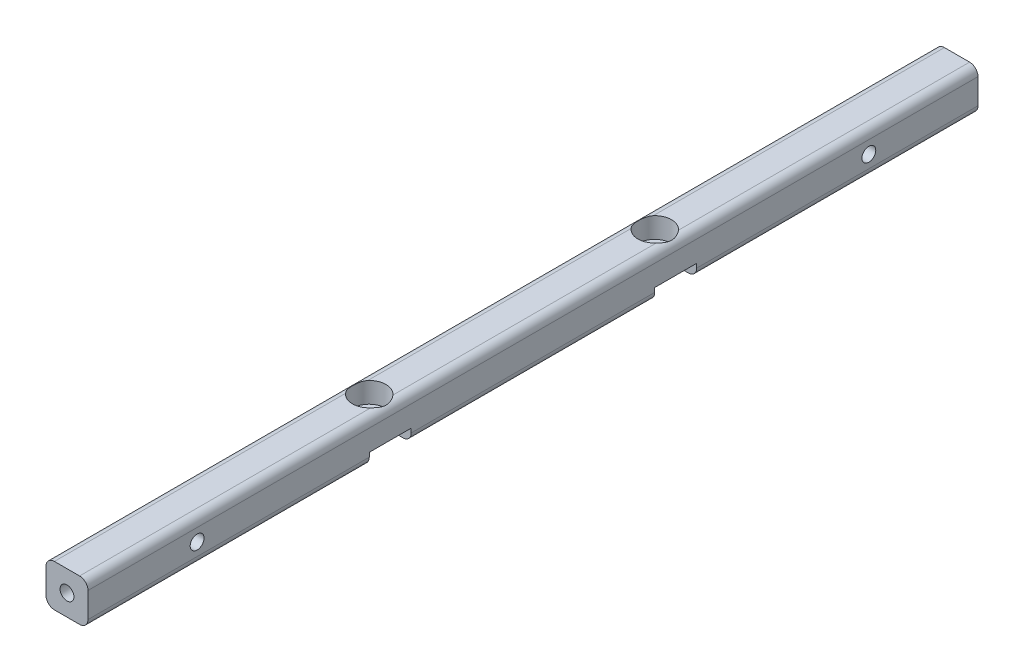
SolidWorks part; units mm, degrees
material "Alliage 1060"
ref_plane "Face" through (0, 0, 0) normal (0, 0, 1) x (1, 0, 0)
ref_plane "Dessus" through (0, 0, 0) normal (0, 1, 0) x (1, 0, 0)
ref_plane "Droite" through (0, 0, 0) normal (1, 0, 0) x (0, 0, -1)
sketch "Esquisse1" plane through (0, 0, 0) normal (0, 0, 1) x (1, 0, 0)
  line L1 (-5, 5) -> (5, 5)
  line L2 (-5, 5) -> (-5, -5)
  line L3 (-5, -5) -> (5, -5)
  line L4 (5, 5) -> (5, -5)
extrude "Boss.-Extru.1" add sketch "Esquisse1" along normal mid plane 212
hole_wizard "Trou taraudé M41" positions "Esquisse3" profile "Esquisse2" tap size "M4" standard "Iso"
sketch "Esquisse3" plane through (0, 0, 106) normal (0, 0, 1) x (1, 0, 0)
  point P0 (0, 0)
sketch "Esquisse2" plane through (0, 0, 106) normal (1, 0, 0) x (0, -1, 0)
  line L0 (0, 0) -> (0, 12.4914)
  line L1 (0, 12.4914) -> (1.65, 11.5)
  line L2 (1.65, 11.5) -> (1.65, 0)
  line L5 (1.65, 0) -> (0, 0)
  line L10 (0, 12.4914) -> (-1.65, 11.5) construction
  line L11 (0, -6.35) -> (0, 107.95) construction
  dimension "Diamètre du trou pour taraudage" = 3.3
  dimension "Profondeur du trou pour taraudage" = 11.5
  dimension "Angle de pointe" = 118
cosmetic thread "Filetage de perçage1" parameters "D1"=8, "D2"=4
hole_wizard "Trou taraudé M42" positions "Esquisse5" profile "Esquisse4" tap size "M4" standard "Iso"
sketch "Esquisse5" plane through (0, 0, -106) normal (0, 0, -1) x (-1, 0, 0)
  point P0 (0, 0)
sketch "Esquisse4" plane through (0, 0, -106) normal (1, 0, 0) x (0, 1, 0)
  line L0 (0, 0) -> (0, 12.4914)
  line L1 (0, 12.4914) -> (1.65, 11.5)
  line L2 (1.65, 11.5) -> (1.65, 0)
  line L5 (1.65, 0) -> (0, 0)
  line L10 (0, 12.4914) -> (-1.65, 11.5) construction
  line L11 (0, -6.35) -> (0, 107.95) construction
  dimension "Diamètre du trou pour taraudage" = 3.3
  dimension "Profondeur du trou pour taraudage" = 11.5
  dimension "Angle de pointe" = 118
cosmetic thread "Filetage de perçage2" parameters "D1"=8, "D2"=4
fillet "Congé1" radius 2 4 edges at (-5, -5, 0) (5, -5, 0) (-5, 5, 0) (5, 5, 0)
hole_wizard "Chambrage pour vis à tête hexagonale M41" positions "Esquisse7" profile "Esquisse6" counterbore size "M4" standard "Iso" end condition through all
sketch "Esquisse7" plane through (0, 5, 0) normal (0, 1, 0) x (1, 0, 0)
  point P0 (0, 34)
  point P13 (0, -34)
  dimension "D1" = 34
  dimension "D2" = 34
sketch "Esquisse6" plane through (0, 5, -34) normal (1, 0, 0) x (0, 0, 1)
  line L0 (0, 0) -> (0, 10)
  line L1 (0, 10) -> (2.15, 10)
  line L3 (2.15, 10) -> (2.15, 4.9)
  line L4 (2.15, 4.9) -> (4, 4.9)
  line L5 (4, 4.9) -> (4, 0)
  line L7 (4, 0) -> (0, 0)
  line L11 (0, -6.35) -> (0, 107.95) construction
  dimension "Diamètre du perçage jusqu'au prochain" = 4.3
  dimension "Profondeur du perçage jusqu'au prochain" = 10
  dimension "Diamètre du chambrage" = 8
  dimension "Profondeur du chambrage" = 4.9
sketch "Esquisse8" plane through (5, 0, 0) normal (1, 0, 0) x (0, 0, -1)
  line L0 (29, -10) -> (29, -2)
  line L1 (29, -2) -> (39, -2)
  line L2 (39, -2) -> (39, -10)
  line L3 (39, -10) -> (29, -10)
  line L4 (34, 10) -> (34, -10) construction
  line L5 (106, -5) -> (-106, -5) construction
  line L6 (-29, -10) -> (-39, -10)
  line L7 (-29, -2) -> (-29, -10)
  line L8 (-34, 10) -> (-34, -10) construction
  line L9 (-39, -10) -> (-39, -2)
  line L10 (-39, -2) -> (-29, -2)
  dimension "D1" = 34
  dimension "D2" = 5
  dimension "D3" = 5
  dimension "D4" = 3
  dimension "D5" = 34
extrude "Enlèv. mat.-Extru.1" cut sketch "Esquisse8" against normal up to next
hole_wizard "Trou taraudé M44" positions "Esquisse12" profile "Esquisse11" tap size "M4" standard "Iso" end condition up to next
sketch "Esquisse12" plane through (5, 0, 0) normal (1, 0, 0) x (0, 0, -1)
  point P0 (-80, 0)
  point P4 (80, 0)
  dimension "D1" = 80
  dimension "D2" = 80
sketch "Esquisse11" plane through (5, 0, 80) normal (0, 1, 0) x (0, 0, -1)
  line L0 (0, 0) -> (0, 10)
  line L1 (0, 10) -> (1.65, 10)
  line L2 (1.65, 10) -> (1.65, 0)
  line L5 (1.65, 0) -> (0, 0)
  line L11 (0, -6.35) -> (0, 107.95) construction
  dimension "Diamètre du trou pour taraudage jusqu'au prochain" = 3.3
  dimension "Profondeur du trou pour taraudage jusqu'au prochain" = 10
cosmetic thread "Filetage de perçage6" parameters "D2"=4
cosmetic thread "Filetage de perçage7" parameters "D2"=4
